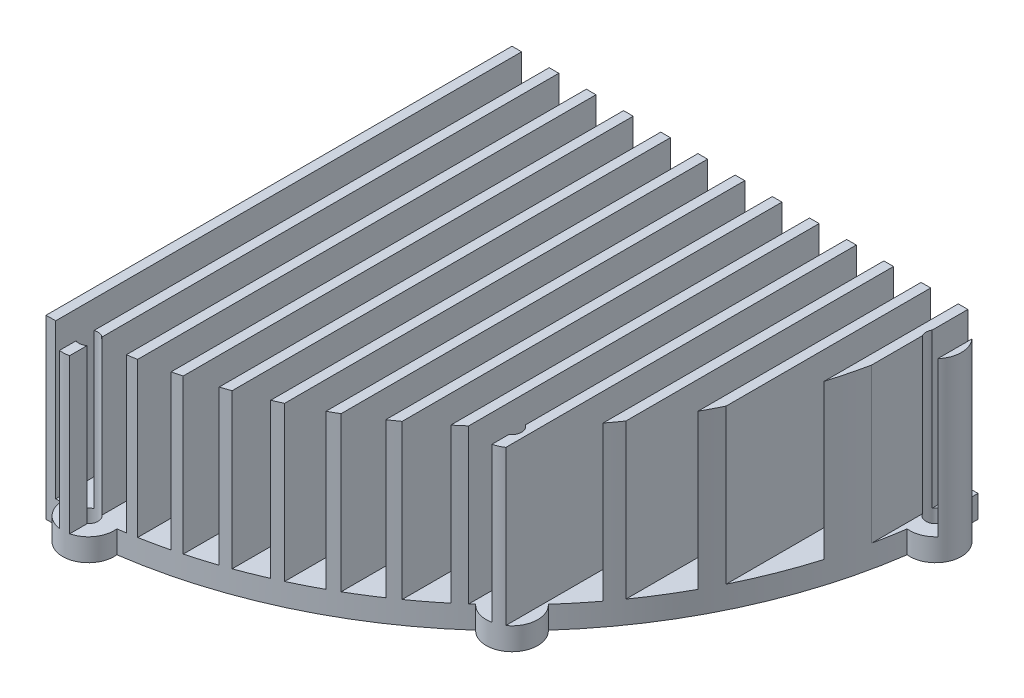
SolidWorks part; units mm, degrees
ref_plane "Ön Düzlem" through (0, 0, 0) normal (0, 0, 1) x (1, 0, 0)
ref_plane "Üst Düzlem" through (0, 0, 0) normal (0, 1, 0) x (1, 0, 0)
ref_plane "Sağ Düzlem" through (0, 0, 0) normal (1, 0, 0) x (0, 0, -1)
sketch "Sketch1" plane through (0, 0, 0) normal (0, 0, 1) x (1, 0, 0)
  line L0 (11.5714, 7) -> (11.5714, 55)
  line L1 (0, 0) -> (165, 0)
  line L2 (0, 0) -> (0, 7)
  line L3 (3, 7) -> (11.5714, 7)
  line L4 (165, 0) -> (165, 10)
  line L6 (0, 7) -> (0, 55)
  line L7 (0, 55) -> (3, 55)
  line L8 (3, 7) -> (3, 55)
  line L10 (14.5714, 7) -> (14.5714, 55)
  line L11 (11.5714, 55) -> (14.5714, 55)
  line L12 (23.1429, 7) -> (23.1429, 55)
  line L14 (26.1429, 7) -> (26.1429, 55)
  line L15 (23.1429, 55) -> (26.1429, 55)
  line L16 (34.7143, 7) -> (34.7143, 55)
  line L18 (37.7143, 7) -> (37.7143, 55)
  line L19 (34.7143, 55) -> (37.7143, 55)
  line L20 (46.2857, 7) -> (46.2857, 55)
  line L22 (49.2857, 7) -> (49.2857, 55)
  line L23 (46.2857, 55) -> (49.2857, 55)
  line L24 (57.8571, 7) -> (57.8571, 55)
  line L26 (60.8571, 7) -> (60.8571, 55)
  line L27 (57.8571, 55) -> (60.8571, 55)
  line L28 (69.4286, 7) -> (69.4286, 55)
  line L30 (72.4286, 7) -> (72.4286, 55)
  line L31 (69.4286, 55) -> (72.4286, 55)
  line L32 (81, 7) -> (81, 55)
  line L34 (84, 7) -> (84, 55)
  line L35 (81, 55) -> (84, 55)
  line L36 (92.5714, 7) -> (92.5714, 55)
  line L38 (95.5714, 7) -> (95.5714, 55)
  line L39 (92.5714, 55) -> (95.5714, 55)
  line L40 (104.1429, 7) -> (104.1429, 55)
  line L42 (107.1429, 7) -> (107.1429, 55)
  line L43 (104.1429, 55) -> (107.1429, 55)
  line L44 (115.7143, 7) -> (115.7143, 55)
  line L46 (118.7143, 7) -> (118.7143, 55)
  line L47 (115.7143, 55) -> (118.7143, 55)
  line L48 (127.2857, 7) -> (127.2857, 55)
  line L50 (130.2857, 7) -> (130.2857, 55)
  line L51 (127.2857, 55) -> (130.2857, 55)
  line L52 (138.8571, 7) -> (138.8571, 55)
  line L54 (141.8571, 7) -> (141.8571, 55)
  line L55 (138.8571, 55) -> (141.8571, 55)
  line L56 (150.4286, 7) -> (150.4286, 55)
  line L58 (153.4286, 7) -> (153.4286, 55)
  line L59 (150.4286, 55) -> (153.4286, 55)
  line L60 (162, 7) -> (162, 55)
  line L62 (165, 7) -> (165, 55)
  line L63 (162, 55) -> (165, 55)
  line L78 (14.5714, 7) -> (23.1429, 7)
  line L79 (26.1429, 7) -> (34.7143, 7)
  line L80 (37.7143, 7) -> (46.2857, 7)
  line L81 (49.2857, 7) -> (57.8571, 7)
  line L82 (60.8571, 7) -> (69.4286, 7)
  line L83 (72.4286, 7) -> (81, 7)
  line L84 (84, 7) -> (92.5714, 7)
  line L85 (95.5714, 7) -> (104.1429, 7)
  line L86 (107.1429, 7) -> (115.7143, 7)
  line L87 (118.7143, 7) -> (127.2857, 7)
  line L88 (130.2857, 7) -> (138.8571, 7)
  line L89 (141.8571, 7) -> (150.4286, 7)
  line L90 (153.4286, 7) -> (162, 7)
  dimension "D1" = 165
  dimension "D2" = 7
  dimension "D3" = 48
  dimension "D4" = 3
  dimension "D5" = 15
extrude "Boss-Extrude1" add sketch "Sketch1" along normal blind 1000 contours L90 L58 L59 L56 L89 L54 L55 L52 L88 L50 L51 L48 L87 L46 L47 L44 L86 L42 L43 L40 L85 L38 L39 L36 L84 L34 L35 L32 L83 L30 L31 L28 L82 L26 L27 L24 L81 L22 L23 L20 L80 L18 L19 L16 L79 L14 L15 L12 L78 L10 L11
sketch "Sketch2" plane through (0, 0, 0) normal (0, -1, 0) x (1, 0, 0)
  line L0 (0, 145) -> (0, 0)
  line L1 (0, 0) -> (145, 0)
  line L2 (0, 0) -> (102.5305, 102.5305) construction
  line L3 (0, 0) -> (12.6376, 144.4482) construction
  line L4 (0, 0) -> (144.4482, 12.6376) construction
  arc A0 (135, 0) -> (0, 135) centre (0, 0) ccw construction
  arc A1 (145, 0) -> (144.9254, 4.6518) centre (0, 0) ccw
  circle A2 centre (12.6376, 144.4482) radius 3
  circle A3 centre (102.5305, 102.5305) radius 3
  circle A4 centre (144.4482, 12.6376) radius 3
  arc A5 (20.5849, 143.5314) -> (4.6518, 144.9254) centre (12.6376, 144.4482) ccw
  arc A6 (108.0291, 96.7197) -> (96.7197, 108.0291) centre (102.5305, 102.5305) ccw
  arc A7 (144.9254, 4.6518) -> (143.5314, 20.5849) centre (144.4482, 12.6376) ccw
  arc A8 (4.6518, 144.9254) -> (0, 145) centre (0, 0) ccw
  arc A9 (104.6297, 100.3873) -> (100.3873, 104.6297) centre (0, 0) ccw
  arc A10 (96.7197, 108.0291) -> (20.5849, 143.5314) centre (0, 0) ccw
  arc A11 (143.5314, 20.5849) -> (108.0291, 96.7197) centre (0, 0) ccw
  arc A12 (144.6788, 9.6465) -> (144.1559, 15.6233) centre (0, 0) ccw
  line M14 (0, 0) -> (165, 0)
  line M15 (165, 0) -> (165, 1000)
  line M16 (165, 1000) -> (0, 1000)
  line M17 (0, 1000) -> (0, 0)
  dimension "D1" = 270
  dimension "D2" = 290
  dimension "D3" = 6
  dimension "D4" = 6
  dimension "D5" = 6
  dimension "D8" = 16
  dimension "D9" = 16
  dimension "D10" = 16
  dimension "D6" = 5
  dimension "D7" = 5
  dimension "D11" = 45
extrude "Cut-Extrude2" cut sketch "Sketch2" against normal through all contours A11 A7 A1 A8 A5 A10 A6 M14 M15 M16 M17 | A12 A4 | A4 A12 | A9 A3 | A3 A9 | A2
